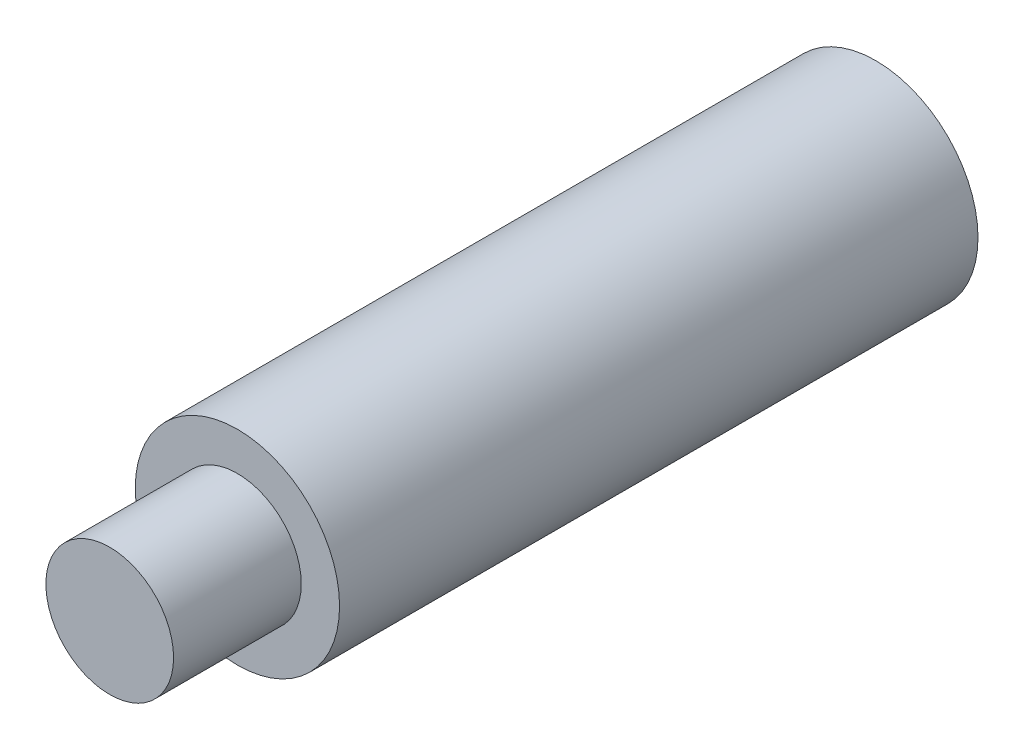
SolidWorks part; units mm, degrees
ref_plane "Front Plane" through (0, 0, 0) normal (0, 0, 1) x (1, 0, 0)
ref_plane "Top Plane" through (0, 0, 0) normal (0, 1, 0) x (1, 0, 0)
ref_plane "Right Plane" through (0, 0, 0) normal (1, 0, 0) x (0, 0, -1)
sketch "Sketch1" plane through (0, 0, 0) normal (0, 0, 1) x (1, 0, 0)
  circle A0 centre (0, 0) radius 4
  dimension "D1" = 8
extrude "Boss-Extrude1" add sketch "Sketch1" along normal blind 25
sketch "Sketch2" plane through (0, 0, 25) normal (0, 0, 1) x (1, 0, 0)
  circle A0 centre (0, 0) radius 2.5
  dimension "D1" = 5
extrude "Boss-Extrude2" add sketch "Sketch2" along normal blind 5
